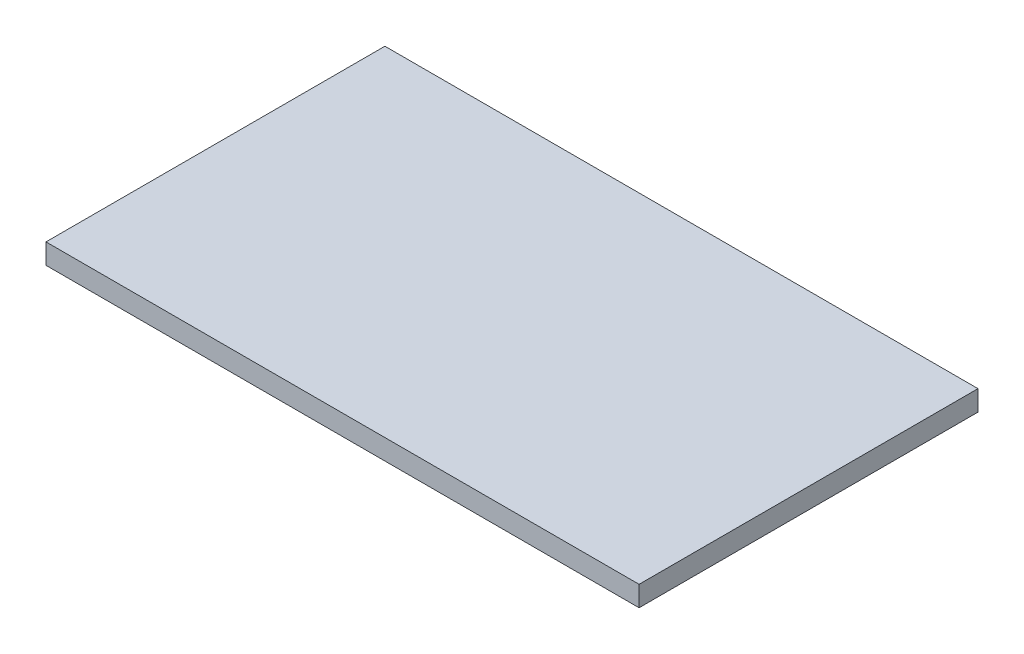
SolidWorks part; units mm, degrees
material "Pine"
ref_plane "Front Plane" through (0, 0, 0) normal (0, 0, 1) x (1, 0, 0)
ref_plane "Top Plane" through (0, 0, 0) normal (0, 1, 0) x (1, 0, 0)
ref_plane "Right Plane" through (0, 0, 0) normal (1, 0, 0) x (0, 0, -1)
sketch "Sketch1" plane through (0, 0, 0) normal (0, 1, 0) x (1, 0, 0)
  line L1 (0, 0) -> (175, 0)
  line L2 (0, 0) -> (0, 100)
  line L3 (0, 100) -> (175, 100)
  line L4 (175, 0) -> (175, 100)
  dimension "D1" = 175
  dimension "D2" = 100
extrude "Boss-Extrude1" add sketch "Sketch1" along normal blind 6
equation "\"BoardThickness\"= 6"
equation "\"D1@Boss-Extrude1\"=\"BoardThickness\""
